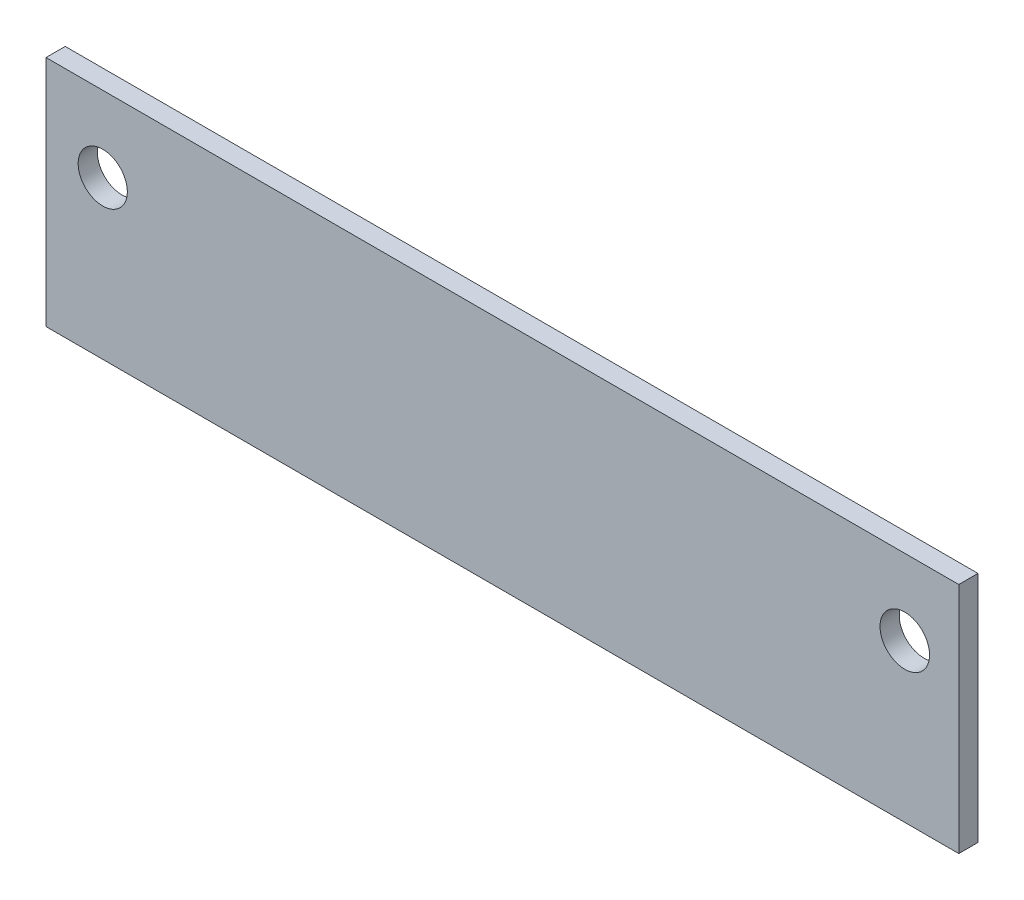
SolidWorks part; units mm, degrees
material "1060 Alloy"
ref_plane "Front Plane" through (0, 0, 0) normal (0, 0, 1) x (1, 0, 0)
ref_plane "Top Plane" through (0, 0, 0) normal (0, 1, 0) x (1, 0, 0)
ref_plane "Right Plane" through (0, 0, 0) normal (1, 0, 0) x (0, 0, -1)
sketch "Sketch1" plane through (0, 0, 0) normal (0, 0, 1) x (1, 0, 0)
  line L1 (-60.5, 0) -> (60.1369, 0)
  line L2 (-60.5, 0) -> (-60.5, -30.7998)
  line L3 (-60.5, -30.7998) -> (60.1369, -30.7998)
  line L4 (60.1369, 0) -> (60.1369, -30.7998)
  circle A0 centre (53, -10) radius 3.2734
  circle A1 centre (-53, -10) radius 3.25
extrude "Boss-Extrude1" add sketch "Sketch1" along normal blind 2.54
